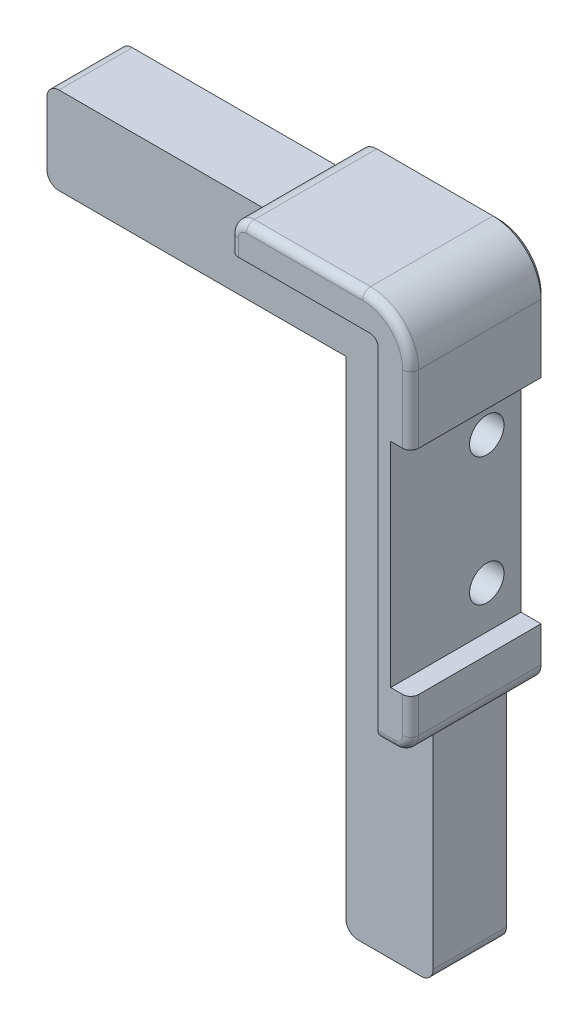
SolidWorks part; units mm, degrees
ref_plane "Front Plane" through (0, 0, 0) normal (0, 0, 1) x (1, 0, 0)
ref_plane "Top Plane" through (0, 0, 0) normal (0, 1, 0) x (1, 0, 0)
ref_plane "Right Plane" through (0, 0, 0) normal (1, 0, 0) x (0, 0, -1)
ref_plane "PZ 20.375" through (0, 0, 20.375) normal (0, 0, 1) x (1, 0, 0)
sketch "body and tongues sketch" plane through (0, 0, 20.375) normal (0, 0, 1) x (1, 0, 0)
  line L0 (4.42, 7.07) -> (-18.08, 7.07)
  line L1 (-18.08, 7.07) -> (-18.08, 2.75)
  line L2 (-18.08, 2.75) -> (-48.08, 2.75)
  line L3 (-48.08, 2.75) -> (-48.08, -8.13)
  line L4 (-48.08, -8.13) -> (-10.78, -8.13)
  line L5 (-10.78, -8.13) -> (-10.78, -70.43)
  line L6 (-10.78, -70.43) -> (0.1, -70.43)
  line L7 (0.1, -70.43) -> (0.1, -40.43)
  line L8 (0.1, -40.43) -> (4.42, -40.43)
  line L9 (4.42, -40.43) -> (4.42, 7.07)
extrude "body and tongues" add sketch "body and tongues sketch" along normal mid plane 9.75
ref_plane "PZ 23.935" through (0, 0, 23.935) normal (0, 0, 1) x (1, 0, 0)
sketch "rim sketch" plane through (0, 0, 23.935) normal (0, 0, 1) x (1, 0, 0)
  line L0 (4.42, 7.07) -> (-18.08, 7.07)
  line L1 (-18.08, 7.07) -> (-18.08, 3)
  line L2 (-18.08, 3) -> (0.35, 3)
  line L3 (0.35, 3) -> (0.35, -40.43)
  line L4 (0.35, -40.43) -> (4.42, -40.43)
  line L5 (4.42, -40.43) -> (4.42, 7.07)
extrude "rim" add sketch "rim sketch" along normal mid plane 16.87
sketch "bracket seat sketch" plane through (0, 0, 23.935) normal (0, 0, 1) x (1, 0, 0)
  line L0 (1.92, -34) -> (5.42, -34)
  line L1 (5.42, -34) -> (5.42, -7.4)
  line L2 (5.42, -7.4) -> (1.92, -7.4)
  line L3 (1.92, -7.4) -> (1.92, -34)
extrude "bracket seat" cut sketch "bracket seat sketch" against normal mid plane 18.87
ref_plane "PX -1.580" through (-1.58, 0, 0) normal (1, 0, 0) x (0, 0, -1)
sketch "screw pilots sketch" plane through (-1.58, 0, 0) normal (1, 0, 0) x (0, 0, -1)
  circle A0 centre (-20.375, -28.7) radius 2.15
  circle A1 centre (-20.375, -12.7) radius 2.15
extrude "screw pilots" cut sketch "screw pilots sketch" against normal mid plane 9
fillet "bumper corner" radius 6 1 edges at (4.42, 7.07, 23.935)
fillet "inside corner of the rim" radius 1 1 edges at (0.35, 3, 28.81)
fillet "rim ends" radius 2 2 edges at (4.42, -40.43, 23.935) (-18.08, 7.07, 23.935)
fillet "tongue lead-in" radius 1.5 4 edges at (-48.08, -8.13, 20.375) (-48.08, 2.75, 20.375) (-10.78, -70.43, 20.375) (0.1, -70.43, 20.375)
fillet "rim top edge" radius 1 7 edges at (4.42, -36.215, 32.37) (2.6626, 5.3126, 32.37) (-18.08, 4.035, 32.37) (-17.4942, 6.4842, 32.37) (1.385, -40.43, 32.37) (3.8342, -39.8442, 32.37) (-8.83, 7.07, 32.37)
chamfer "bed face chamfer" distance 0.6 angle 45 20 edges at (-10.78, -38.53, 15.5) (-10.3407, -69.9907, 15.5) (-5.34, -70.43, 15.5) (-0.3393, -69.9907, 15.5) (0.1, -54.68, 15.5) (1.26, -40.43, 15.5) (3.8342, -39.8442, 15.5) (4.42, -3.165, 15.5) (3.17, -34, 15.5) (1.92, -20.7, 15.5) (3.17, -7.4, 15.5) (2.6626, 5.3126, 15.5) (-8.83, 7.07, 15.5) (-17.4942, 6.4842, 15.5) (-18.08, 3.91, 15.5) (-32.33, 2.75, 15.5) (-47.6407, 2.3107, 15.5) (-48.08, -2.69, 15.5) (-47.6407, -7.6907, 15.5) (-28.68, -8.13, 15.5)
equation "\"diffL\" = 608.8mm"
equation "\"diffW\" = 329.4mm"
equation "\"diffT\" = 2.9mm"
equation "\"chanSlotW\" = 12.9mm"
equation "\"chanSlotDepth\" = 11.13mm"
equation "\"chanFloor\" = 1.57mm"
equation "\"chanLeg\" = 12.7mm"
equation "\"lightL\" = 605mm"
equation "\"lightW\" = 331mm"
equation "\"lightH\" = 92mm"
equation "\"lightSideFlat\" = 30mm"
equation "\"lightSlopeLen\" = 33.1mm"
equation "\"lightWingDepth\" = 47.9mm"
equation "\"lightWingFlat\" = 90.2mm"
equation "\"lightChanW\" = 99.6mm"
equation "\"lightChanStand\" = 44.1mm"
equation "\"insFlangeD\" = 12.3mm"
equation "\"insFromEnd\" = 20.7mm"
equation "\"insUpSlope\" = 20.8mm"
equation "\"gaugeH\" = 10mm"
equation "\"gaugeStepLen\" = 14mm"
equation "\"gaugeStepW0\" = 13.1mm"
equation "\"gaugeStepDW\" = 0.2mm"
equation "\"gaugeSteps\" = 5mm"
equation "\"gaugeHandleLen\" = 30mm"
equation "\"gaugeHandleW\" = 24mm"
equation "\"gaugeSlot0\" = 3mm"
equation "\"gaugeSlotD\" = 0.1mm"
equation "\"gaugeSlotDepth\" = 8mm"
equation "\"gap\" = 25.4mm"
equation "\"edgeL\" = 1mm"
equation "\"edgeW\" = 0.75mm"
equation "\"proud\" = 1.5mm"
equation "\"seatClr\" = 0.15mm"
equation "\"tongueClrZ\" = 0.1mm"
equation "\"tongueClrX\" = 0.25mm"
equation "\"tongueLen\" = 30mm"
equation "\"armSide\" = 45mm"
equation "\"armEnd\" = 20mm"
equation "\"cornerCham\" = 3mm"
equation "\"brkW\" = 26mm"
equation "\"brkT\" = 7mm"
equation "\"brkSeatClr\" = 0.2mm"
equation "\"brkScrewSpan\" = 16mm"
equation "\"pilotD\" = 2.7mm"
equation "\"pilotDepth\" = 10mm"
equation "\"screwClrD\" = 3.9mm"
equation "\"jogBelow\" = 4mm"
equation "\"padT\" = 7mm"
equation "\"padLen\" = 31mm"
equation "\"m6Clr\" = 7mm"
equation "\"m6Slot\" = 3mm"
equation "\"flangeRelD\" = 17mm"
equation "\"flangeRelDepth\" = 1.5mm"
equation "\"relLen\" = 7mm"
equation "\"relDepth\" = 4mm"
equation "\"relLand\" = 2mm"
equation "\"knockN\" = 100mm"
equation "\"petgcfE\" = 3000mm"
equation "\"mockExtent\" = 110mm"
equation "\"relZnear\" = 9.4mm"
equation "\"relZfar\" = 23.4mm"
equation "\"headD\" = 8mm"
equation "\"headH\" = 2.5mm"
equation "\"headFromEnd\" = 6.8mm"
equation "\"headBack\" = 16.4mm"
equation "\"sideClr\" = 0.4mm"
equation "\"cornerRelR\" = 1.5mm"
equation "\"cornerRelBack\" = 0.6mm"
equation "\"endHeadH\" = 2.8mm"
equation "\"footClr\" = 1.2mm"
equation "\"footEndClr\" = 3.5mm"
equation "\"footLift\" = 6mm"
equation "\"footBlockClr\" = 0.5mm"
equation "\"footBack\" = 50mm"
equation "\"footFwd\" = 10mm"
equation "\"footBraceEnd\" = 3mm"
equation "\"footLoadN\" = 25mm"
equation "\"spacerLen\" = 60mm"
equation "\"spacerShort\" = 0.5mm"
equation "\"spacerCham\" = 0.8mm"
equation "\"spacerPerSide\" = 3mm"
equation "\"spacerPerEnd\" = 1mm"
equation "\"toolR\" = 9mm"
equation "\"visR\" = 4mm"
equation "\"edgeR\" = 1mm"
equation "\"bendOutR\" = 5mm"
equation "\"insideR\" = 2.5mm"
equation "\"footCornerR\" = 10mm"
equation "\"footFrontR\" = 8mm"
equation "\"braceKinkR\" = 12mm"
equation "\"bedCham\" = 1mm"
equation "\"bedChamSmall\" = 0.6mm"
equation "\"soleTopR\" = 2mm"
equation "\"cornerR\" = 6mm"
equation "\"rimInR\" = 1mm"
equation "\"insFlangeH\" = 1mm"
equation "\"insHoleFinishD\" = 4.5mm"
equation "\"insLen\" = 6.4mm"
